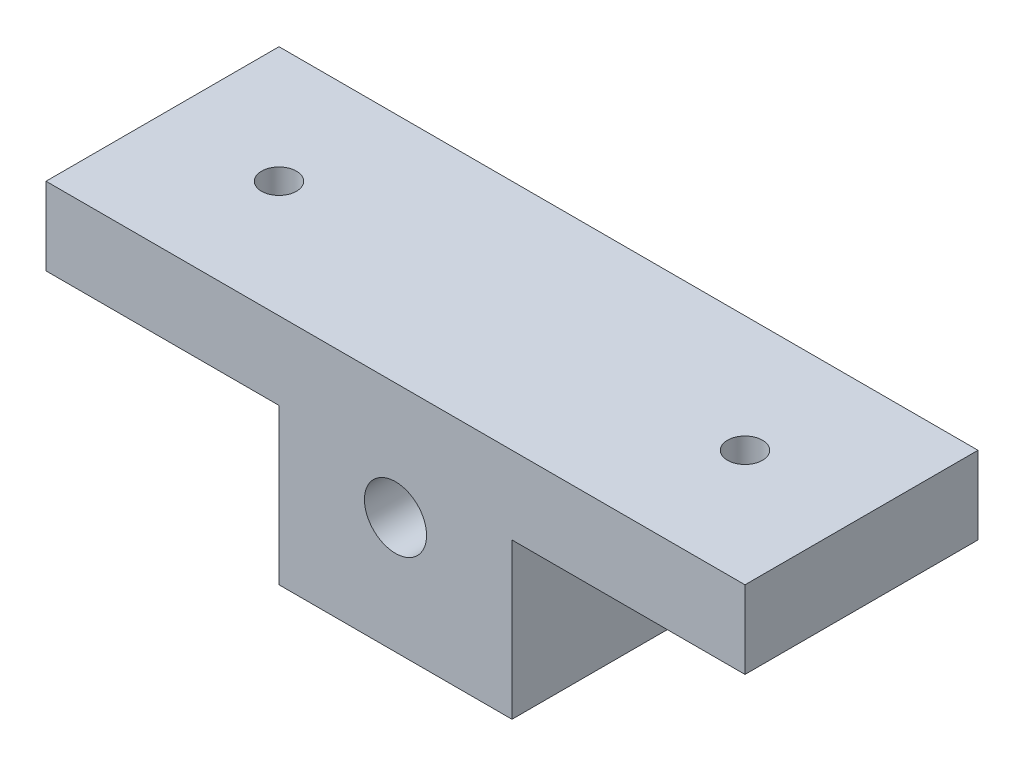
SolidWorks part; units mm, degrees
ref_plane "정면" through (0, 0, 0) normal (0, 0, 1) x (1, 0, 0)
ref_plane "윗면" through (0, 0, 0) normal (0, 1, 0) x (1, 0, 0)
ref_plane "우측면" through (0, 0, 0) normal (1, 0, 0) x (0, 0, -1)
sketch "스케치1" plane through (0, 0, 0) normal (0, 0, 1) x (1, 0, 0)
  line L1 (-15, 15) -> (15, 15)
  line L2 (-15, 15) -> (-15, -15)
  line L3 (-15, -15) -> (15, -15)
  line L4 (15, 15) -> (15, -15)
  line L5 (-15, 15) -> (15, -15) construction
  line L6 (-15, -15) -> (15, 15) construction
  point P0 (0, 0)
  dimension "D1" = 30
  dimension "D2" = 30
extrude "보스-돌출1" add sketch "스케치1" along normal blind 30
sketch "스케치2" plane through (0, 0, 30) normal (0, 0, 1) x (1, 0, 0)
  circle A0 centre (0, 0) radius 4
  dimension "D1" = 8
extrude "컷-돌출1" cut sketch "스케치2" against normal blind 30
sketch "스케치3" plane through (15, 0, 0) normal (1, 0, 0) x (0, 0, -1)
  line L0 (0, -15) -> (0, 15) construction
  line L1 (-30, 15) -> (0, 15)
  line L2 (-30, 15) -> (-30, 5)
  line L3 (-30, 5) -> (0, 5)
  line L4 (0, 15) -> (0, 5)
  dimension "D1" = 10
extrude "보스-돌출2" add sketch "스케치3" along normal blind 30
sketch "스케치4" plane through (-15, 0, 0) normal (-1, 0, 0) x (0, 0, 1)
  line L0 (30, 15) -> (30, -15) construction
  line L1 (0, 15) -> (30, 15)
  line L2 (0, 15) -> (0, 5)
  line L3 (0, 5) -> (30, 5)
  line L4 (30, 15) -> (30, 5)
  dimension "D1" = 10
extrude "보스-돌출3" add sketch "스케치4" along normal blind 30
hole_wizard "M4 소켓 머리 캡 나사용 카운터보어1" positions "스케치7" profile "스케치8" counterbore size "M4" standard "KS" end condition through all
sketch "스케치7" plane through (0, 5, 0) normal (0, -1, 0) x (-1, 0, 0)
  line L0 (-45, -30) -> (-45, 0) construction
  line L1 (-45, 0) -> (-15, 0) construction
  line L2 (45, 0) -> (45, -30) construction
  line L3 (45, 0) -> (15, 0) construction
  point P0 (-30, -15)
  point P2 (30, -15)
  dimension "D1" = 15
  dimension "D2" = 15
  dimension "D3" = 15
  dimension "D4" = 15
sketch "스케치8" plane through (30, 5, 15) normal (1, 0, 0) x (0, 0, -1)
  line L0 (0, 0) -> (0, 10)
  line L1 (0, 10) -> (2.25, 10)
  line L3 (2.25, 10) -> (2.25, 4)
  line L4 (2.25, 4) -> (5, 4)
  line L5 (5, 4) -> (5, 0)
  line L7 (5, 0) -> (0, 0)
  line L11 (0, -6.35) -> (0, 107.95) construction
  dimension "관통 구멍 지름" = 4.5
  dimension "관통 구멍 깊이" = 10
  dimension "카운터보어 지름" = 10
  dimension "카운터보어 깊이" = 4
